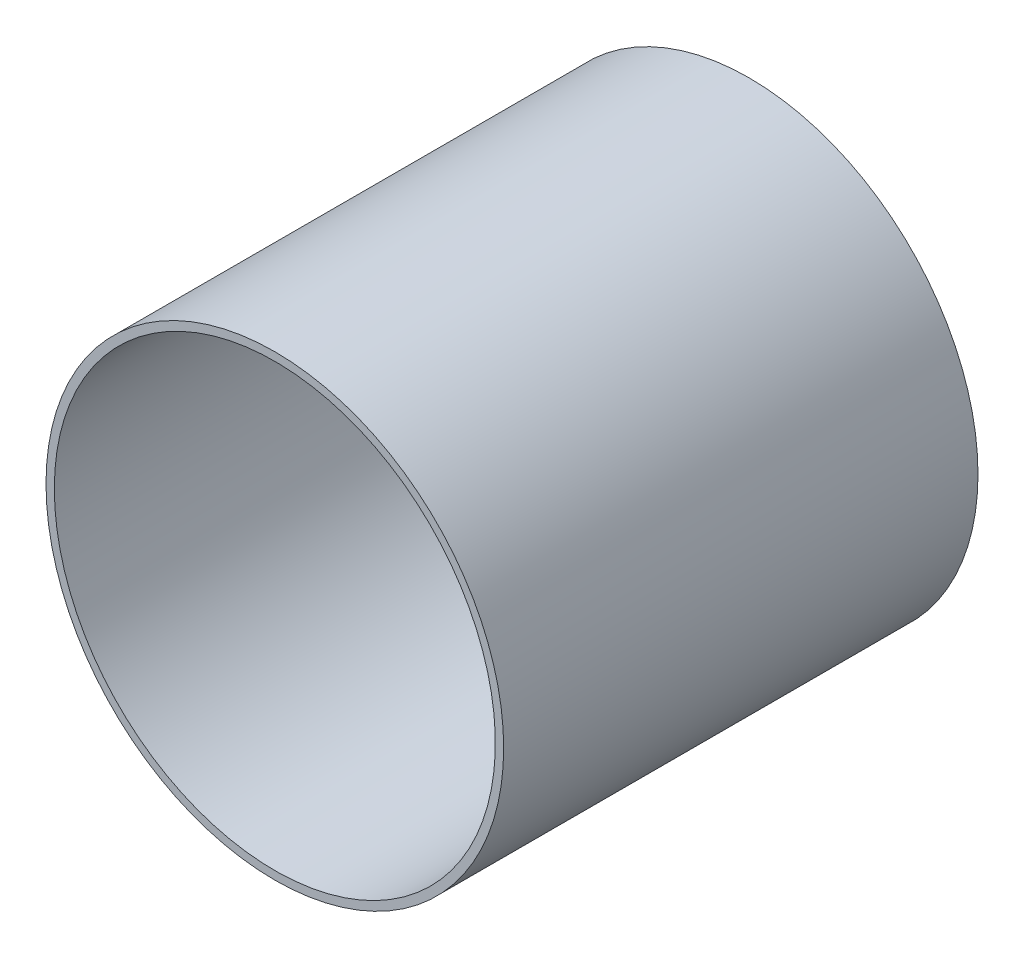
SolidWorks part; units mm, degrees
ref_plane "Face" through (0, 0, 0) normal (0, 0, 1) x (1, 0, 0)
ref_plane "Dessus" through (0, 0, 0) normal (0, 1, 0) x (1, 0, 0)
ref_plane "Droite" through (0, 0, 0) normal (1, 0, 0) x (0, 0, -1)
sketch "Esquisse1" plane through (0, 0, 0) normal (0, 0, 1) x (1, 0, 0)
  circle A0 centre (0, 0) radius 27.5
  circle A1 centre (0, 0) radius 26.5
  dimension "D1" = 53
  dimension "D2" = 55
extrude "Extrusion1" add sketch "Esquisse1" along normal blind 57
